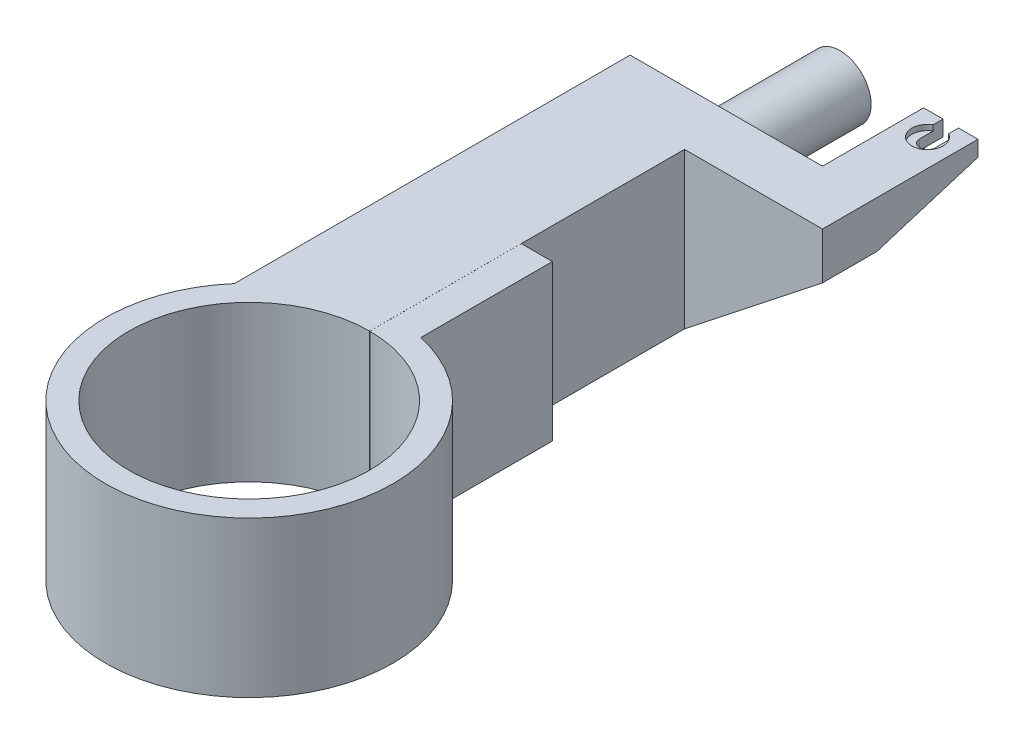
SolidWorks part; units mm, degrees
ref_plane "Front Plane" through (0, 0, 0) normal (0, 0, 1) x (1, 0, 0)
ref_plane "Top Plane" through (0, 0, 0) normal (0, 1, 0) x (1, 0, 0)
ref_plane "Right Plane" through (0, 0, 0) normal (1, 0, 0) x (0, 0, -1)
sketch "Sketch1" plane through (0, 0, 0) normal (0, 1, 0) x (1, 0, 0)
  line L0 (0, -15.5) -> (0, -63)
  line L1 (0, 18.5) -> (0, 15.5)
  line L2 (-14, -12.0934) -> (-14, -63)
  line L3 (-11, -60) -> (-11, -14.8745)
  line L4 (-3, -60) -> (-3, -18.2551)
  line L6 (-14, -63) -> (0, -63)
  line L8 (-11, -60) -> (-3, -60)
  arc A0 (0, 15.5) -> (0, -15.5) centre (0, 0) ccw
  arc A1 (0, 18.5) -> (-14, -12.0934) centre (0, 0) ccw
  arc A2 (-11, -14.8745) -> (-3, -18.2551) centre (0, 0) ccw
  dimension "D3" = 15.5
  dimension "D4" = 3
  dimension "D1" = 3
  dimension "D2" = 3
  dimension "D5" = 8
  dimension "D6" = 63
  dimension "D7" = 3
extrude "Boss-Extrude1" add sketch "Sketch1" along normal blind 20 contours A0 L0 L6 L4 A2 L3 L2 A1 L1
sketch "Sketch2" plane through (0, 0, 63) normal (0, 0, 1) x (1, 0, 0)
  line L0 (0, 10) -> (-14, 10) construction
  line L1 (0, 20) -> (0, 0) construction
  line L2 (-14, 20) -> (-14, 0) construction
  line L3 (-7, 20) -> (-7, 0) construction
  line L4 (-14, 20) -> (0, 20) construction
  line L5 (-14, 0) -> (0, 0) construction
  circle A0 centre (-7, 10) radius 4
  dimension "D1" = 8
extrude "Boss-Extrude2" add sketch "Sketch2" along normal blind 20
sketch "Sketch3" plane through (0, 20, 0) normal (0, 1, 0) x (1, 0, 0)
  line L0 (0, -63) -> (10.7494, -63)
  line L1 (10.7494, -63) -> (10.7494, -76)
  line L2 (10.7494, -76) -> (13.2494, -76)
  line L3 (17.7494, -76) -> (17.7494, -56)
  line L4 (17.7494, -56) -> (0, -56)
  line L5 (0, -63) -> (0, -15.5) construction
  line L6 (0, -56) -> (0, -63)
  line L7 (2, -58) -> (15.7494, -58)
  line L8 (15.7494, -58) -> (15.7494, -69)
  line L9 (2, -58) -> (2, -61)
  line L10 (2, -61) -> (12.7494, -61)
  line L11 (12.7494, -61) -> (12.7494, -69)
  line L12 (14.2494, -76) -> (14.2494, -73) construction
  line L13 (15.2494, -73) -> (15.2494, -76)
  line L14 (13.2494, -73) -> (13.2494, -76)
  line L15 (15.2494, -76) -> (17.7494, -76)
  line L16 (12.7494, -69) -> (15.7494, -69)
  line L17 (-3, -73) -> (14.2494, -73) construction
  line L18 (-3, -83) -> (-3, -63) construction
  line L19 (10.7494, -69.5) -> (17.7494, -69.5) construction
  line L20 (14.2494, -69.5) -> (14.2494, -73) construction
  arc A0 (15.2494, -73) -> (13.2494, -73) centre (14.2494, -73) ccw
  dimension "D1" = 2
  dimension "D2" = 3
  dimension "D3" = 2
  dimension "D4" = 2
  dimension "D5" = 2
  dimension "D6" = 2
  dimension "D7" = 2
  dimension "D8" = 7
  dimension "D9" = 7
  dimension "D13" = 7
extrude "Boss-Extrude3" add sketch "Sketch3" against normal blind 2
sketch "Sketch4" plane through (0, 18, 0) normal (0, -1, 0) x (1, 0, 0)
  line L0 (15.7494, 58) -> (2, 58) construction
  line L1 (15.7494, 69) -> (15.7494, 58) construction
  line L2 (12.7494, 69) -> (15.7494, 69) construction
  line L3 (12.7494, 61) -> (12.7494, 69) construction
  line L4 (2, 61) -> (12.7494, 61) construction
  line L5 (2, 58) -> (2, 61) construction
  line L6 (15.7494, 58) -> (2, 58)
  line L7 (15.7494, 69) -> (15.7494, 58)
  line L8 (12.7494, 69) -> (15.7494, 69)
  line L9 (0, 63) -> (0, 56)
  line L10 (0, 56) -> (17.7494, 56)
  line L11 (17.7494, 56) -> (17.7494, 76)
  line L12 (17.7494, 76) -> (15.2494, 76)
  line L13 (15.2494, 76) -> (15.2494, 73)
  line L14 (13.2494, 73) -> (13.2494, 76)
  line L15 (13.2494, 76) -> (10.7494, 76)
  line L16 (10.7494, 76) -> (10.7494, 63)
  line L17 (10.7494, 63) -> (0, 63)
  line L18 (0, 63) -> (0, 56)
  line L19 (0, 56) -> (17.7494, 56)
  line L20 (10.7494, 63) -> (10.7494, 66)
  line L21 (10.7494, 63) -> (10.7494, 76) construction
  line L22 (17.7494, 66) -> (17.7494, 76)
  line L23 (17.7494, 56) -> (17.7494, 66)
  line L24 (17.7494, 76) -> (17.7494, 56) construction
  line L25 (17.7494, 76) -> (15.7494, 76)
  line L26 (10.7494, 63) -> (0, 63)
  line L27 (12.7494, 61) -> (12.7494, 69)
  line L28 (2, 61) -> (12.7494, 61)
  line L29 (2, 58) -> (2, 61)
  line L30 (15.2494, 76) -> (17.7494, 76) construction
  line L31 (15.7494, 76) -> (15.7494, 69)
  line L32 (10.7494, 66) -> (10.7494, 76)
  line L33 (10.7494, 76) -> (12.7494, 76)
  line L34 (10.7494, 76) -> (13.2494, 76) construction
  line L35 (12.7494, 76) -> (12.7494, 69)
  arc A1 (13.2494, 73) -> (15.2494, 73) centre (14.2494, 73) ccw
  dimension "D1" = 0
extrude "Boss-Extrude4" add sketch "Sketch4" along normal up to surface (18 mm away) up to face at (-8.887, 0, 19.1831)
sketch "Sketch5" plane through (0, 0, 56) normal (0, 0, -1) x (-1, 0, 0)
  line L0 (0, 0) -> (-17.7494, 14)
  line L1 (-17.7494, 0) -> (-17.7494, 20) construction
  line L2 (-17.7494, 14) -> (-17.7494, -1.5545)
  line L3 (-17.7494, -1.5545) -> (0, -1.5545)
  line L4 (0, -1.5545) -> (0, 0)
  line L5 (-17.7494, 20) -> (0, 20) construction
  dimension "D1" = 6
extrude "Cut-Extrude1" cut sketch "Sketch5" against normal blind 22
sketch "Sketch7" plane through (0, 20, 0) normal (0, 1, 0) x (1, 0, 0)
  line L0 (2, -61) -> (12.7494, -61) construction
  line L1 (2, -58) -> (2, -61) construction
  line L2 (15.7494, -58) -> (2, -58) construction
  line L3 (15.7494, -69) -> (15.7494, -58) construction
  line L4 (12.7494, -69) -> (15.7494, -69) construction
  line L5 (12.7494, -61) -> (12.7494, -69) construction
  line L6 (2, -61) -> (12.7494, -61)
  line L7 (2, -58) -> (2, -61)
  line L8 (15.7494, -58) -> (2, -58)
  line L9 (15.7494, -69) -> (15.7494, -58)
  line L10 (12.7494, -69) -> (15.7494, -69)
  line L11 (12.7494, -61) -> (12.7494, -69)
extrude "Boss-Extrude5" add sketch "Sketch7" against normal up to surface (2 mm away)
sketch "Sketch8" plane through (0, 20, 0) normal (0, 1, 0) x (1, 0, 0)
  circle A0 centre (14.2494, -73) radius 2
  dimension "D1" = 4
extrude "Cut-Extrude3" cut sketch "Sketch8" against normal blind 0.7
sketch "Sketch6" plane through (17.7494, 0, 0) normal (1, 0, 0) x (0, 0, -1)
  line L0 (-76, 14) -> (-56, 14) construction
  line L2 (-63, 14) -> (-82.697, 14)
  line L3 (-82.697, 14) -> (-82.697, 0.4151)
  line L4 (-82.697, 0.4151) -> (-63, 0.4151)
  line L5 (-63, 14) -> (-63, 6) construction
  line L6 (-63, 0.4151) -> (-63, 14)
extrude "Cut-Extrude2" cut sketch "Sketch6" against normal up to surface (7 mm away) up to face at (10.7494, 14.2393, 69.5)
sketch "Sketch10" plane through (17.7494, 0, 0) normal (1, 0, 0) x (0, 0, -1)
  line L0 (-63, 14) -> (-76, 18)
  line L1 (-76, 14) -> (-76, 20) construction
  line L2 (-76, 18) -> (-76, 12.2169)
  line L3 (-76, 12.2169) -> (-63, 12.2169)
  line L4 (-63, 12.2169) -> (-63, 14)
extrude "Cut-Extrude4" cut sketch "Sketch10" against normal up to surface (7 mm away) up to face at (10.7494, 17, 69.5)
sketch "Sketch11" plane through (0, 20, 0) normal (0, 1, 0) x (1, 0, 0)
  line L0 (-11, -14.8745) -> (-11, -60) construction
  line L1 (-3, -60) -> (-3, -18.2551) construction
  line L2 (-11, -60) -> (-3, -60) construction
  line L3 (-11, -14.8745) -> (-11, -60)
  line L4 (-3, -60) -> (-3, -18.2551)
  line L5 (-11, -60) -> (-3, -60)
  arc A0 (-11, -14.8745) -> (-3, -18.2551) centre (0, 0) ccw construction
  arc A1 (-11, -14.8745) -> (-3, -18.2551) centre (0, 0) ccw
extrude "Boss-Extrude6" add sketch "Sketch11" against normal blind 2 contours L3 L5 L4 A1
sketch "Sketch12" plane through (0, 0, 0) normal (0, -1, 0) x (1, 0, 0)
  line L0 (-3, 60) -> (-3, 18.2551) construction
  line L1 (-11, 60) -> (-3, 60) construction
  line L2 (-11, 14.8745) -> (-11, 60) construction
  line L3 (-3, 60) -> (-3, 18.2551)
  line L4 (-11, 60) -> (-3, 60)
  line L5 (-11, 14.8745) -> (-11, 60)
  arc A0 (-3, 18.2551) -> (-11, 14.8745) centre (0, 0) ccw construction
  arc A1 (-3, 18.2551) -> (-11, 14.8745) centre (0, 0) ccw
extrude "Boss-Extrude7" add sketch "Sketch12" against normal blind 2
sketch "Sketch13" plane through (0, 20, 0) normal (0, 1, 0) x (1, 0, 0)
  line L0 (0, 15.5) -> (0, 18.5)
  line L1 (0.01, -35) -> (4, -35)
  line L2 (0, -56) -> (0, -15.5) construction
  line L3 (4, -35) -> (4, -18.0624)
  line L4 (0.01, -35) -> (0.01, -15.5)
  arc A0 (0.01, -15.5) -> (0, 15.5) centre (0, 0) ccw
  arc A1 (4, -18.0624) -> (0, 18.5) centre (0, 0) ccw
  dimension "D1" = 4
  dimension "D2" = 0.01
  dimension "D3" = 35
extrude "Boss-Extrude8" add sketch "Sketch13" against normal up to surface (20 mm away) contours A0 L0 A1 L3 L1 L4 up to face at (-7.6175, 0, 24.4427)
ref_plane "Plane1" through (0, 0, 83) normal (0, 0, 1) x (1, 0, 0)
mirror "Mirror2" about plane through (0, 0, 83) normal (0, 0, 1) of bodies 112
sketch "Sketch14" plane through (0, 0, 83) normal (0, 0, 1) x (1, 0, 0)
  line L1 (-55.3555, 39.5134) -> (54.8978, 39.5134)
  line L2 (-55.3555, 39.5134) -> (-55.3555, -25.6766)
  line L3 (-55.3555, -25.6766) -> (54.8978, -25.6766)
  line L4 (54.8978, 39.5134) -> (54.8978, -25.6766)
extrude "Cut-Extrude5" cut sketch "Sketch14" against normal blind 159
